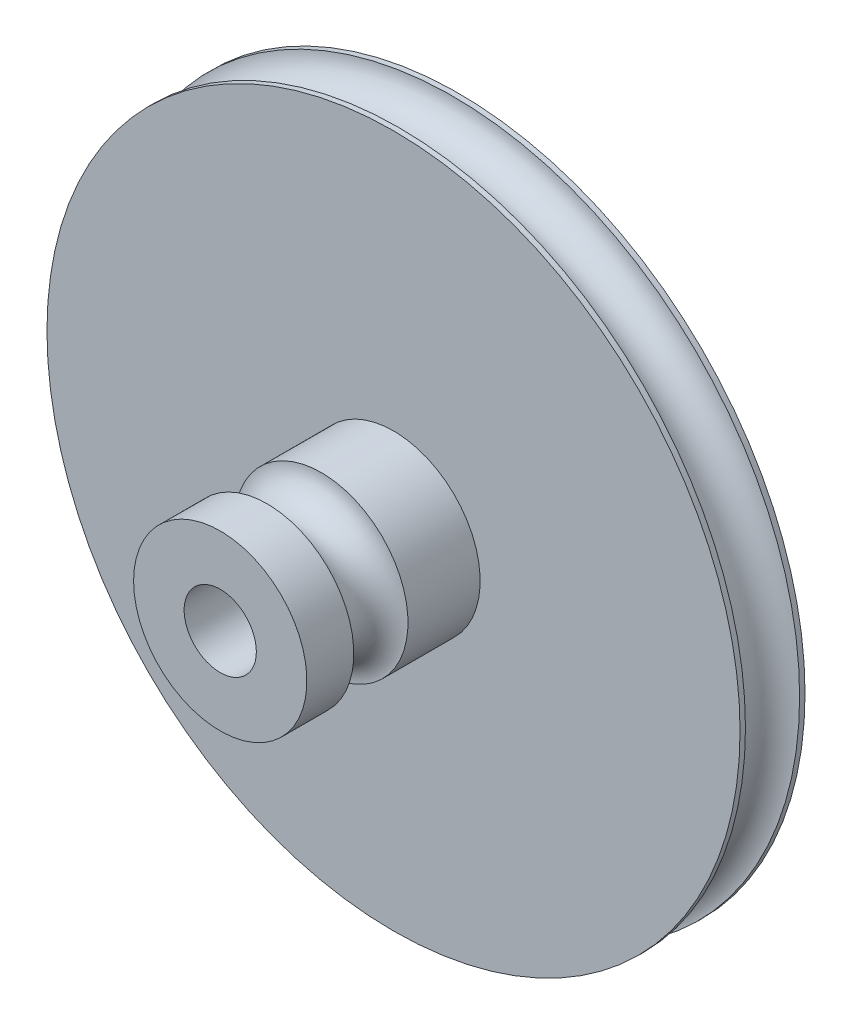
SolidWorks part; units mm, degrees
material "Custom Plastic"
ref_plane "Front Plane" through (0, 0, 0) normal (0, 0, 1) x (1, 0, 0)
ref_plane "Top Plane" through (0, 0, 0) normal (0, 1, 0) x (1, 0, 0)
ref_plane "Right Plane" through (0, 0, 0) normal (1, 0, 0) x (0, 0, -1)
sketch "Sketch1" plane through (0, 0, 0) normal (0, 0, 1) x (1, 0, 0)
  circle A0 centre (0, 0) radius 1.5875
  circle A1 centre (0, 0) radius 15.24
  dimension "D1" = 3.175
  dimension "D2" = 30.48
extrude "Boss-Extrude1" add sketch "Sketch1" along normal blind 2.8575 from offset 5.08 offset against normal yes
sketch "Sketch2" plane through (0, 0, -2.2225) normal (0, 0, 1) x (1, 0, 0)
  circle A0 centre (0, 0) radius 3.81
  circle A1 centre (0, 0) radius 1.5875
  circle A2 centre (0, 0) radius 1.5875 construction
  dimension "D1" = 7.62
extrude "Boss-Extrude2" add sketch "Sketch2" along normal blind 7.62
sketch "Sketch3" plane through (0, 0, 0) normal (0, 1, 0) x (1, 0, 0)
  line L0 (3.81, -5.3975) -> (3.81, 2.2225) construction
  line L1 (15.24, 2.2225) -> (15.24, 5.08) construction
  line L2 (-3.81, -5.3975) -> (3.81, -5.3975) construction
  circle A0 centre (3.81, -2.1431) radius 1.1906
  circle A1 centre (15.24, 3.6513) radius 1.1906
  dimension "D1" = 2.3813
  dimension "D2" = 2.3813
  dimension "D3" = 3.2544
revolve "Cut-Revolve1" cut sketch "Sketch3" angle 360 about axis through (0, 0, -2.2225) along (0, 0, -1)
equation "\"D3@Sketch3\"=\"D2@Sketch3\"/2+0.08125"
